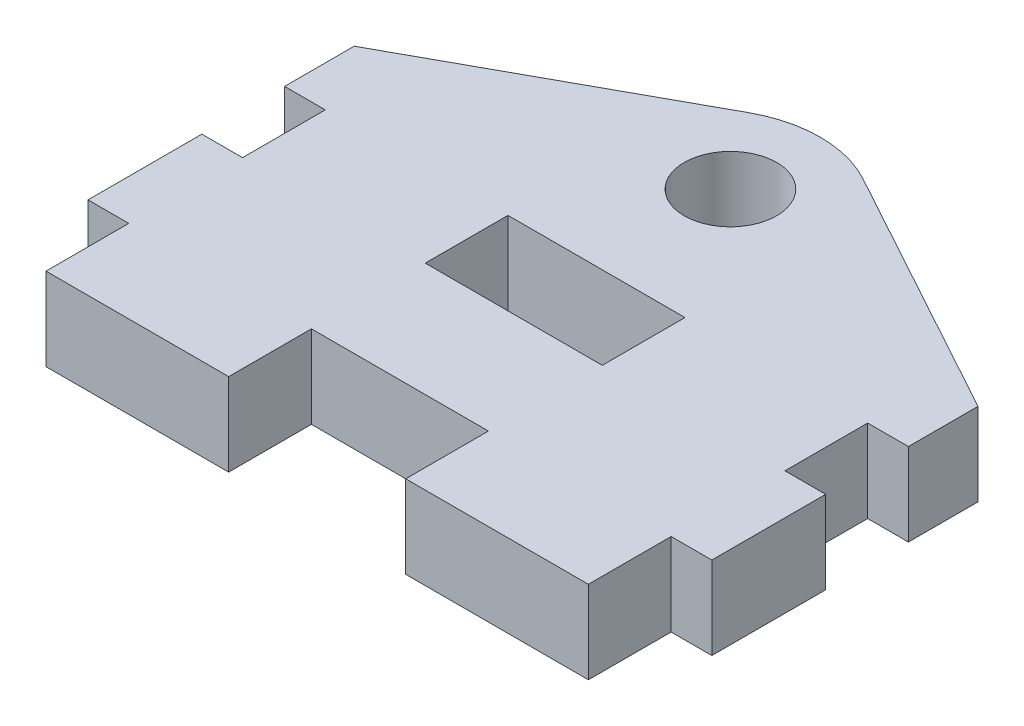
SolidWorks part; units mm, degrees
ref_plane "Front Plane" through (0, 0, 0) normal (0, 0, 1) x (1, 0, 0)
ref_plane "Top Plane" through (0, 0, 0) normal (0, 1, 0) x (1, 0, 0)
ref_plane "Right Plane" through (0, 0, 0) normal (1, 0, 0) x (0, 0, -1)
sketch "Sketch1" plane through (0, 0, 0) normal (0, 1, 0) x (1, 0, 0)
  line L0 (-25.6, 7.9375) -> (-25.6, 0) construction
  line L1 (0, 0) -> (-6.45, 0)
  line L2 (0, 0) -> (0, 8.0375)
  line L3 (0, 8.0375) -> (-6.45, 8.0375)
  line L4 (-50.8, 0) -> (-50.8, 8.0375)
  line L5 (-44.75, 0) -> (-50.8, 0)
  line L6 (-50.8, 4.0187) -> (0, 4.0187) construction
  line L7 (-44.75, 0) -> (-44.75, -5.842)
  line L8 (-44.75, -5.842) -> (-31.85, -5.842)
  line L9 (-31.85, 0) -> (-31.85, -5.842)
  line L10 (-19.35, 0) -> (-19.35, -5.842)
  line L11 (-6.45, -5.842) -> (-19.35, -5.842)
  line L12 (-6.45, 0) -> (-6.45, -5.842)
  line L13 (-6.45, 8.0375) -> (-6.45, 13.8795)
  line L14 (-19.35, 13.8795) -> (-31.85, 13.8795)
  line L15 (-19.35, 8.0375) -> (-19.35, 13.8795)
  line L16 (-31.85, 8.0375) -> (-31.85, 13.8795)
  line L17 (-44.75, 13.8795) -> (-50.8, 13.8795)
  line L18 (-44.75, 8.0375) -> (-44.75, 13.8795)
  line L19 (-19.35, 0) -> (-31.85, 0)
  line L20 (-19.35, 8.0375) -> (-31.85, 8.0375)
  line L21 (-44.75, 8.0375) -> (-50.8, 8.0375)
  line L23 (-0.4, 13.8795) -> (-6.45, 13.8795)
  line L24 (-0.4, 13.8795) -> (-0.4, 17.0545)
  line L25 (-25.6, 7.9375) -> (-25.6, 24.5097) construction
  line L26 (-50.8, 13.8795) -> (-50.8, 17.0545)
  line L30 (-50.8, 17.0545) -> (-29.6397, 28.6544)
  line L33 (-0.4, 17.0545) -> (-21.5603, 28.6544)
  arc A0 (-29.6397, 28.6544) -> (-21.5603, 28.6544) centre (-25.6, 21.2852) cw
  dimension "D1" = 8.0375
  dimension "D2" = 50.8
  dimension "D3" = 5.842
  dimension "D4" = 12.9
  dimension "D5" = 6.25
  dimension "D6" = 3.175
extrude "Boss-Extrude2" add sketch "Sketch1" along normal blind 5.842
hole_wizard "F (0.257) Diameter Hole1" positions "Sketch3" profile "Sketch2" hole size "F" standard "ANSI Inch" end condition through all
sketch "Sketch3" plane through (0, 5.842, 0) normal (0, 1, 0) x (1, 0, 0)
  arc A4 (-21.5603, 28.6544) -> (-29.6397, 28.6544) centre (-25.6, 21.2852) ccw construction
  point P26 (-25.6, 23.339)
  point P34 (-25.6, 29.689)
  dimension "D1" = 6.35
sketch "Sketch2" plane through (-25.6, 5.842, -23.339) normal (1, 0, 0) x (0, 0, 1)
  line L0 (0, 0) -> (0, 5.842)
  line L1 (0, 5.842) -> (3.2639, 5.842)
  line L2 (3.2639, 5.842) -> (3.2639, 0)
  line L5 (3.2639, 0) -> (0, 0)
  line L11 (0, -6.35) -> (0, 107.95) construction
  dimension "Thru Hole Dia." = 6.5278
  dimension "Thru Hole Depth" = 5.842
sketch "Sketch4" plane through (0, 5.842, 0) normal (0, 1, 0) x (1, 0, 0)
  line L1 (-50.8, 0) -> (-44.75, 0) construction
  line L2 (-50.8, 8.0375) -> (-47.625, 8.0375)
  line L3 (-50.8, 8.0375) -> (-50.8, 0)
  line L4 (-50.8, 0) -> (-47.625, 0)
  line L7 (-47.625, 8.0375) -> (-47.625, 0)
  line L8 (-3.575, 9.4954) -> (-3.575, 0)
  line L9 (-0.4, 0) -> (-3.575, 0)
  line L11 (-0.4, 9.4954) -> (-3.575, 9.4954)
  line L12 (-50.8, 13.8795) -> (-47.625, 13.8795)
  line L13 (-0.4, 9.4954) -> (0, 9.4954)
  line L14 (-50.8, 13.8795) -> (-50.8, 20.2295)
  line L15 (-0.4, 0) -> (0, 0)
  line L16 (0, 9.4954) -> (0, 0)
  line L17 (-47.625, 13.8795) -> (-47.625, 20.2295)
  line L18 (-47.625, 20.2295) -> (-50.8, 20.2295)
  line L19 (-0.4, 20.1295) -> (-3.575, 20.1295)
  line L20 (-3.575, 13.7795) -> (-3.575, 20.1295)
  line L21 (-0.4, 13.7795) -> (-3.575, 13.7795)
  line L22 (-0.4, 13.7795) -> (-0.4, 20.1295)
  dimension "D1" = 3.175
  dimension "D2" = 6.35
  dimension "D3" = 6.35
extrude "Cut-Extrude1" cut sketch "Sketch4" against normal through all
